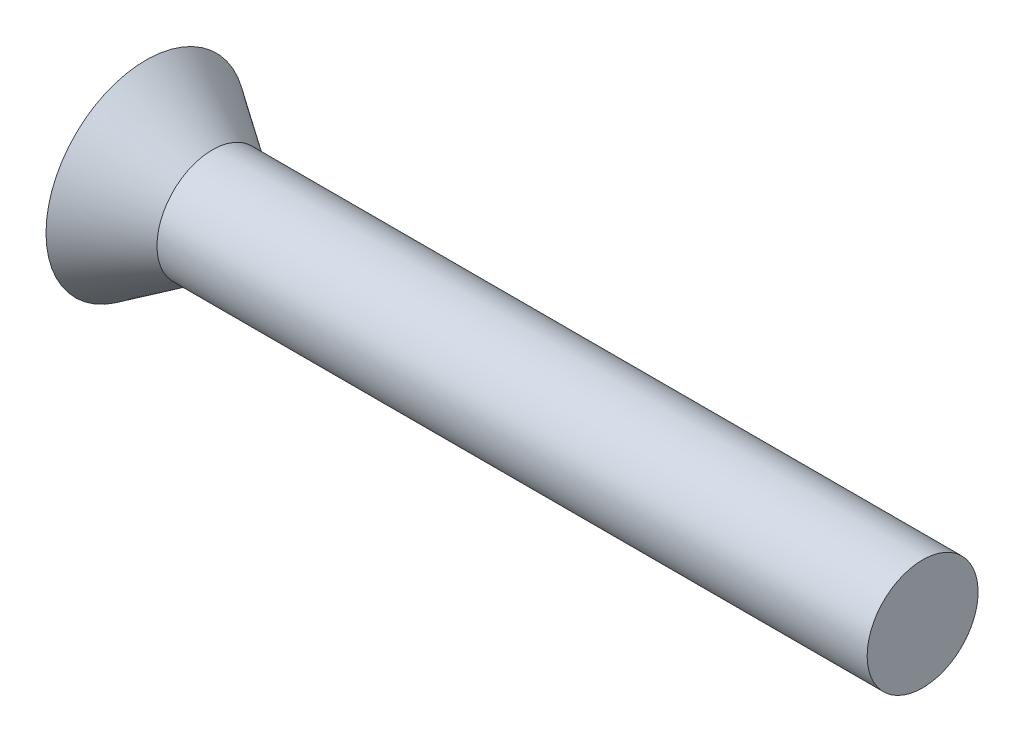
SolidWorks part; units mm, degrees
ref_plane "Front" through (0, 0, 0) normal (0, 0, 1) x (1, 0, 0)
ref_plane "Top" through (0, 0, 0) normal (0, 1, 0) x (1, 0, 0)
ref_plane "Right" through (0, 0, 0) normal (1, 0, 0) x (0, 0, -1)
sketch "Эскиз1" plane through (0, 0, 0) normal (0, 0, 1) x (1, 0, 0)
  line L0 (-51.6306, 0) -> (23.5345, 0) construction
  line L1 (-35, 0) -> (-35, 4.5)
  line L2 (-35, 4.5) -> (-32, 2.5)
  line L3 (-32, 2.5) -> (0, 2.5)
  line L4 (0, 2.5) -> (0, 0)
  line L5 (-35, 0) -> (0, 0)
  dimension "D1" = 35
  dimension "D2" = 2.5
  dimension "D3" = 4.5
  dimension "D4" = 32
revolve "Повернуть1" add sketch "Эскиз1" angle 360 about L0
sketch "Эскиз2" plane through (-35, 0, 0) normal (-1, 0, 0) x (0, 0, 1)
  line L1 (-0.5, 2.25) -> (0.5, 2.25)
  line L2 (-0.5, 2.25) -> (-0.5, -2.25)
  line L3 (-0.5, -2.25) -> (0.5, -2.25)
  line L4 (0.5, 2.25) -> (0.5, -2.25)
  line L5 (-0.5, 2.25) -> (0.5, -2.25) construction
  line L6 (-0.5, -2.25) -> (0.5, 2.25) construction
  line L7 (-2.25, 0.5) -> (2.25, 0.5)
  line L8 (-2.25, 0.5) -> (-2.25, -0.5)
  line L9 (-2.25, -0.5) -> (2.25, -0.5)
  line L10 (2.25, 0.5) -> (2.25, -0.5)
  line L11 (-2.25, 0.5) -> (2.25, -0.5) construction
  line L12 (-2.25, -0.5) -> (2.25, 0.5) construction
  point P0 (0, 0)
  point P6 (0, 0)
  dimension "D1" = 4.5
  dimension "D2" = 4.5
  dimension "D3" = 1
  dimension "D4" = 1
extrude "Вырез-Вытянуть1" cut sketch "Эскиз2" against normal blind 2 contours L2 L7 L4 L1 | L10 L7 L4 L9 | L9 L2 L3 L4 | L8 L9 L2 L7 | L2 L9 L4 L7
